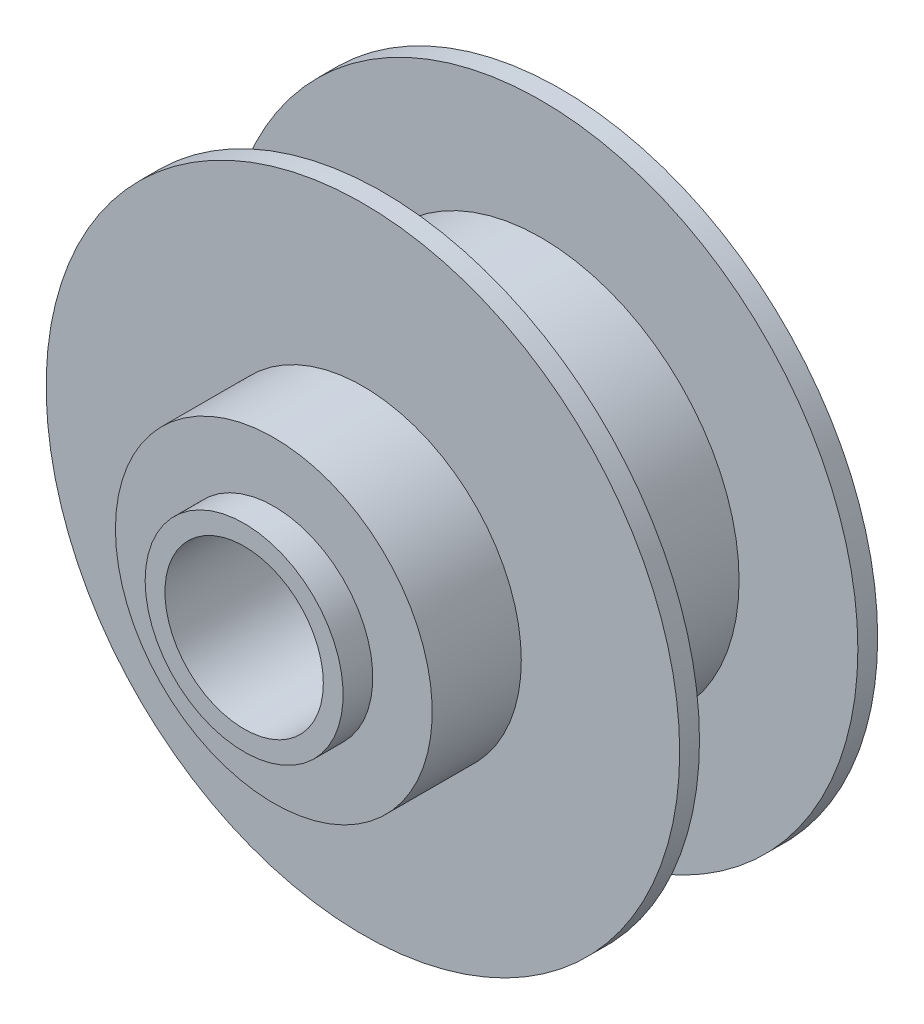
SolidWorks part; units mm, degrees
ref_plane "Plan de face" through (0, 0, 0) normal (0, 0, 1) x (1, 0, 0)
ref_plane "Plan de dessus" through (0, 0, 0) normal (0, 1, 0) x (1, 0, 0)
ref_plane "Plan de droite" through (0, 0, 0) normal (1, 0, 0) x (0, 0, -1)
sketch "Esquisse1" plane through (0, 0, 0) normal (0, 0, 1) x (1, 0, 0)
  circle A0 centre (0, 0) radius 16
  dimension "D1" = 32
extrude "Boss.-Extru.1" add sketch "Esquisse1" along normal blind 10
sketch "Esquisse2" plane through (0, 0, 10) normal (0, 0, 1) x (1, 0, 0)
  circle A0 centre (0, 0) radius 8
  dimension "D1" = 16
extrude "Boss.-Extru.2" add sketch "Esquisse2" along normal blind 6
sketch "Esquisse3" plane through (0, 0, 16) normal (0, 0, 1) x (1, 0, 0)
  circle A0 centre (0, 0) radius 4
  dimension "D1" = 8
extrude "Enlèv. mat.-Extru.1" cut sketch "Esquisse3" against normal through all
sketch "Esquisse4" plane through (0, 0, 0) normal (1, 0, 0) x (0, 0, -1)
  line L0 (0, 16) -> (-10, 16) construction
  line L1 (-9, 16) -> (-1, 16)
  line L2 (-9, 16) -> (-9, 10)
  line L3 (-9, 10) -> (-1, 10)
  line L4 (-1, 16) -> (-1, 10)
  line L5 (0, -16) -> (0, 16) construction
  line L6 (-10, 16) -> (-10, -16) construction
  line L7 (0, 0) -> (7.2899, 0) construction
  dimension "D1" = 6
  dimension "D2" = 1
  dimension "D3" = 1
revolve "Enlèvement de matière-Révolution1" cut sketch "Esquisse4" angle 360 about L7
sketch "Esquisse5" plane through (0, 0, 0) normal (1, 0, 0) x (0, 0, -1)
  line L0 (0, 0) -> (-20.0665, 0) construction
  line L1 (-16, 8) -> (-14.5, 8)
  line L2 (-16, 8) -> (-16, 5)
  line L3 (-16, 5) -> (-14.5, 5)
  line L4 (-14.5, 8) -> (-14.5, 5)
  dimension "D1" = 1.5
  dimension "D2" = 5
revolve "Enlèvement de matière-Révolution2" cut sketch "Esquisse5" angle 360 about L0
